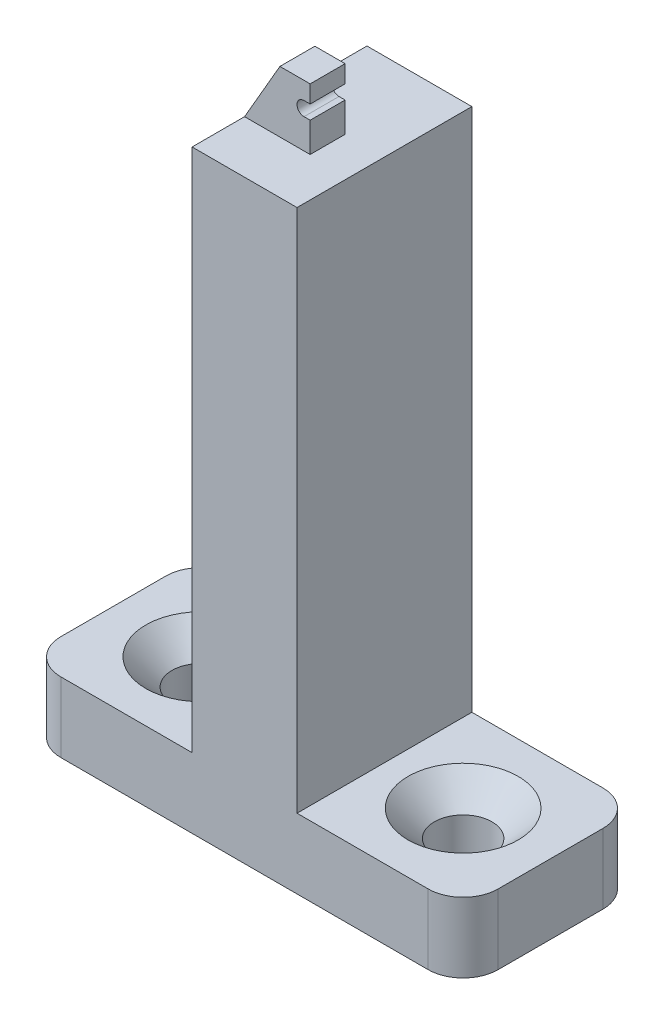
SolidWorks part; units mm, degrees
ref_plane "Front Plane" through (0, 0, 0) normal (0, 0, 1) x (1, 0, 0)
ref_plane "Top Plane" through (0, 0, 0) normal (0, 1, 0) x (1, 0, 0)
ref_plane "Right Plane" through (0, 0, 0) normal (1, 0, 0) x (0, 0, -1)
sketch "Sketch1" plane through (0, 0, 0) normal (0, 1, 0) x (1, 0, 0)
  line L1 (25, 10) -> (-25, 10)
  line L2 (25, 10) -> (25, -10)
  line L3 (25, -10) -> (-25, -10)
  line L4 (-25, 10) -> (-25, -10)
  line L5 (25, 10) -> (-25, -10) construction
  line L6 (25, -10) -> (-25, 10) construction
  point P0 (0, 0)
  dimension "D1" = 50
  dimension "D2" = 20
extrude "Boss-Extrude1" add sketch "Sketch1" along normal blind 8
hole_wizard "CSK for M6 Flat Head Machine Screw1" positions "3DSketch1" profile "Sketch2" countersink size "M6" standard "ANSI Metric" end condition through all
sketch3d "3DSketch1"
  line L0 (-15, 8, 0) -> (15, 8, 0) construction
  point P0 (-15, 8, 0)
  point P2 (15, 8, 0)
  point P20 (0, 8, 0)
  point P22 (19.1681, 8, 0)
  point P23 (15.8413, 8, 0)
  dimension "D1" = 30
sketch "Sketch2" plane through (-15, 8, 0) normal (1, 0, 0) x (0, 0, 1)
  line L0 (0, 0) -> (0, 8)
  line L1 (0, 8) -> (3.3, 8)
  line L2 (3.3, 8) -> (3.3, 3)
  line L3 (3.3, 3) -> (6.3, 0)
  line L5 (6.3, 0) -> (0, 0)
  line L6 (-3.3, 3) -> (-6.3, 0) construction
  line L11 (0, -6.35) -> (0, 107.95) construction
  dimension "Thru Hole Dia." = 6.6
  dimension "Thru Hole Depth" = 8
  dimension "Near C'Sink Dia." = 12.6
  dimension "Near C'Sink Angle" = 90
fillet "Fillet1" radius 4 4 edges at (25, 4, -10) (25, 4, 10) (-25, 4, -10) (-25, 4, 10)
sketch "Sketch3" plane through (0, 8, 0) normal (0, 1, 0) x (1, 0, 0)
  line L0 (-21, -10) -> (21, -10) construction
  line L1 (6, 10) -> (-6, 10)
  line L2 (6, 10) -> (6, -10)
  line L3 (6, -10) -> (-6, -10)
  line L4 (-6, 10) -> (-6, -10)
  line L5 (6, 10) -> (-6, -10) construction
  line L6 (6, -10) -> (-6, 10) construction
  point P0 (0, 0)
  dimension "D1" = 12
extrude "Boss-Extrude2" add sketch "Sketch3" along normal blind 60
sketch "Sketch4" plane through (0, 0, 0) normal (0, 0, 1) x (1, 0, 0)
  line L0 (-6, 68) -> (-1.9585, 75)
  line L1 (-1.9585, 75) -> (1.5, 75)
  line L2 (1.5, 75) -> (1.5, 73)
  line L3 (-6, 68) -> (6, 68) construction
  line L4 (1.5, 68) -> (-6, 68)
  line L5 (0.8, 73) -> (1.5, 73)
  line L6 (0.8, 71.4) -> (1.5, 71.4)
  line L7 (0, 0) -> (0, 87.9265) construction
  line L8 (1.5, 71.4) -> (1.5, 68)
  arc A0 (0.8, 73) -> (0.8, 71.4) centre (0.8, 72.2) ccw
  point P15 (2.2266, 76)
  point P16 (0.6005, 73.4738)
  point P17 (0.5729, 72.208)
  point P18 (-1.4666, 76)
  point P19 (0, 0)
  dimension "D2" = 0.8
  dimension "D1" = 7
  dimension "D3" = 1.5
  dimension "D4" = 5
  dimension "D5" = 60
extrude "Boss-Extrude3" add sketch "Sketch4" along normal blind 4
